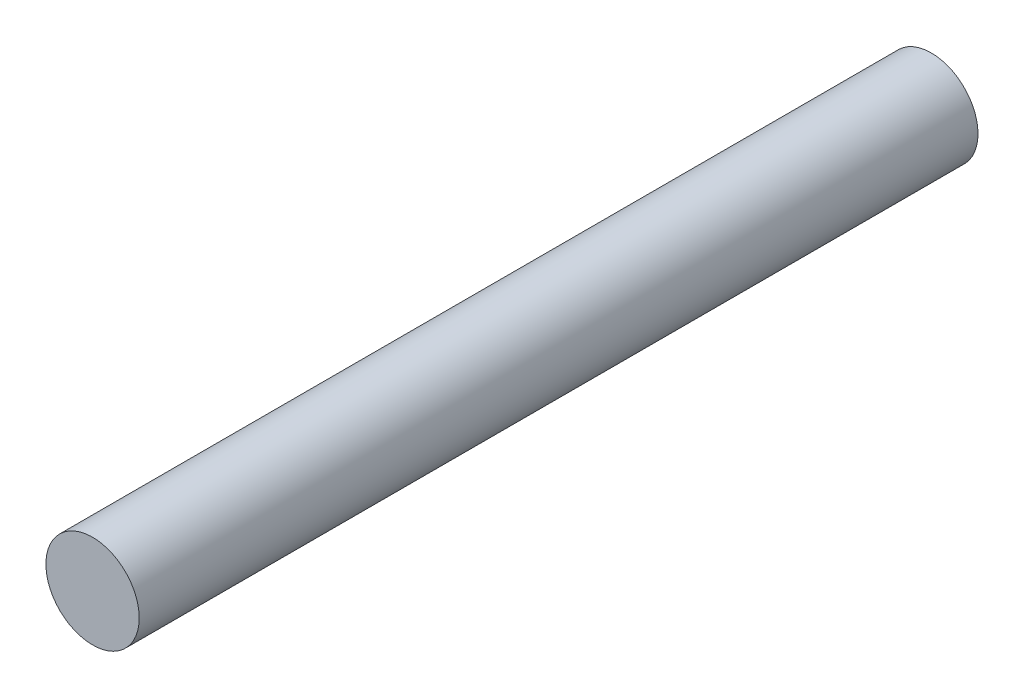
SolidWorks part; units mm, degrees
ref_plane "Front Plane" through (0, 0, 0) normal (0, 0, 1) x (1, 0, 0)
ref_plane "Top Plane" through (0, 0, 0) normal (0, 1, 0) x (1, 0, 0)
ref_plane "Right Plane" through (0, 0, 0) normal (1, 0, 0) x (0, 0, -1)
sketch "Sketch1" plane through (0, 0, 0) normal (0, 0, 1) x (1, 0, 0)
  circle A0 centre (0, 0) radius 4.95
  dimension "D1" = 9.9
extrude "Boss-Extrude1" add sketch "Sketch1" along normal blind 87 and the other way blind 2
